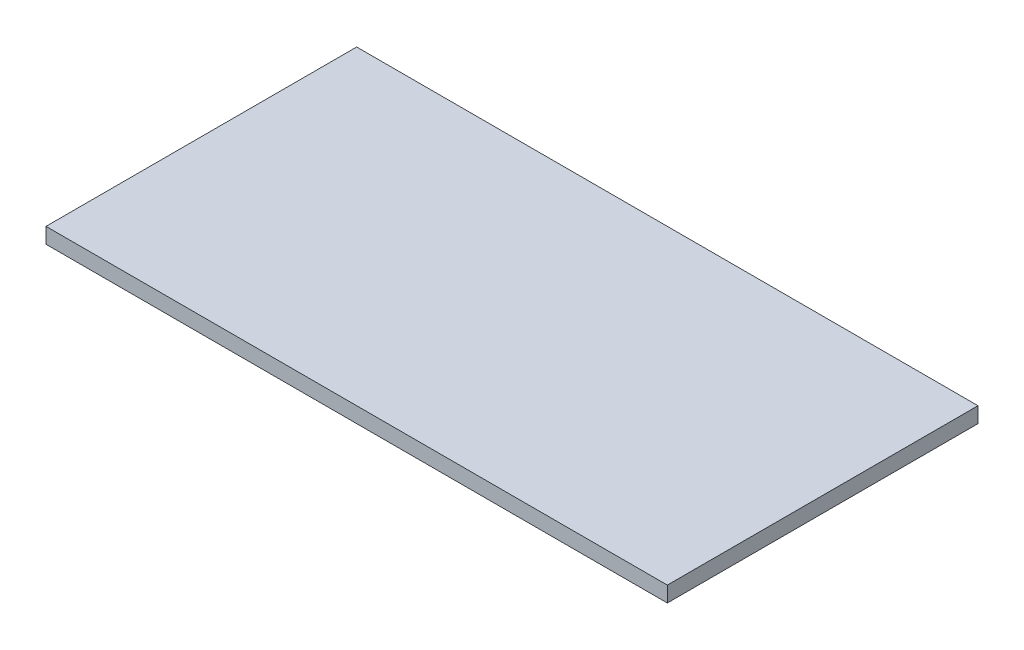
SolidWorks part; units mm, degrees
material "ABS"
ref_plane "Front Plane" through (0, 0, 0) normal (0, 0, 1) x (1, 0, 0)
ref_plane "Top Plane" through (0, 0, 0) normal (0, 1, 0) x (1, 0, 0)
ref_plane "Right Plane" through (0, 0, 0) normal (1, 0, 0) x (0, 0, -1)
sketch "Sketch1" plane through (0, 0, 0) normal (0, 1, 0) x (1, 0, 0)
  line L1 (0, 0) -> (80, 0)
  line L2 (0, 0) -> (0, -40)
  line L3 (0, -40) -> (80, -40)
  line L4 (80, 0) -> (80, -40)
  dimension "D1" = 80
  dimension "D2" = 40
extrude "Boss-Extrude1" add sketch "Sketch1" along normal blind 2
